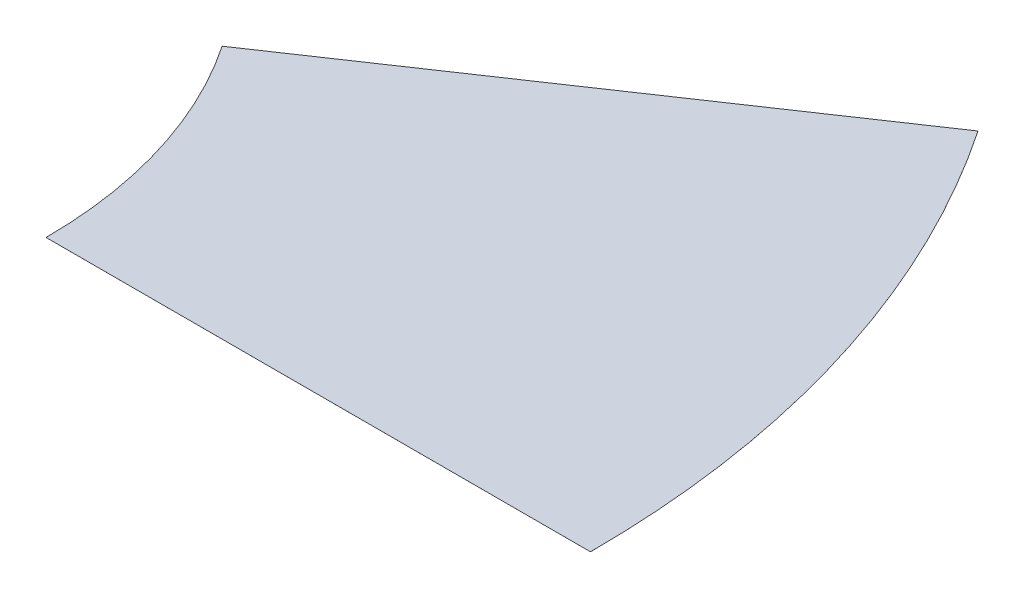
SolidWorks part; units mm, degrees
ref_plane "Front" through (0, 0, 0) normal (0, 0, 1) x (1, 0, 0)
ref_plane "Top" through (0, 0, 0) normal (0, 1, 0) x (1, 0, 0)
ref_plane "Right" through (0, 0, 0) normal (1, 0, 0) x (0, 0, -1)
sketch "草图1" plane through (0, 0, 0) normal (0, 1, 0) x (1, 0, 0)
  line L0 (0, 0) -> (110, 0) construction
  line L1 (91.1941, 61.5112) -> (0, 0) construction
  line L2 (91.1941, 61.5112) -> (41.4519, 27.9596)
  line L3 (110, 0) -> (50, 0)
  arc A0 (110, 0) -> (91.1941, 61.5112) centre (0, 0) ccw
  arc A1 (50, 0) -> (41.4519, 27.9596) centre (0, 0) ccw
  dimension "D2" = 50
  dimension "D3" = 110
  dimension "D1" = 34
extrude "凸台-拉伸1" add sketch "草图1" along normal blind 0.001 contours L3 A1 L2 A0
